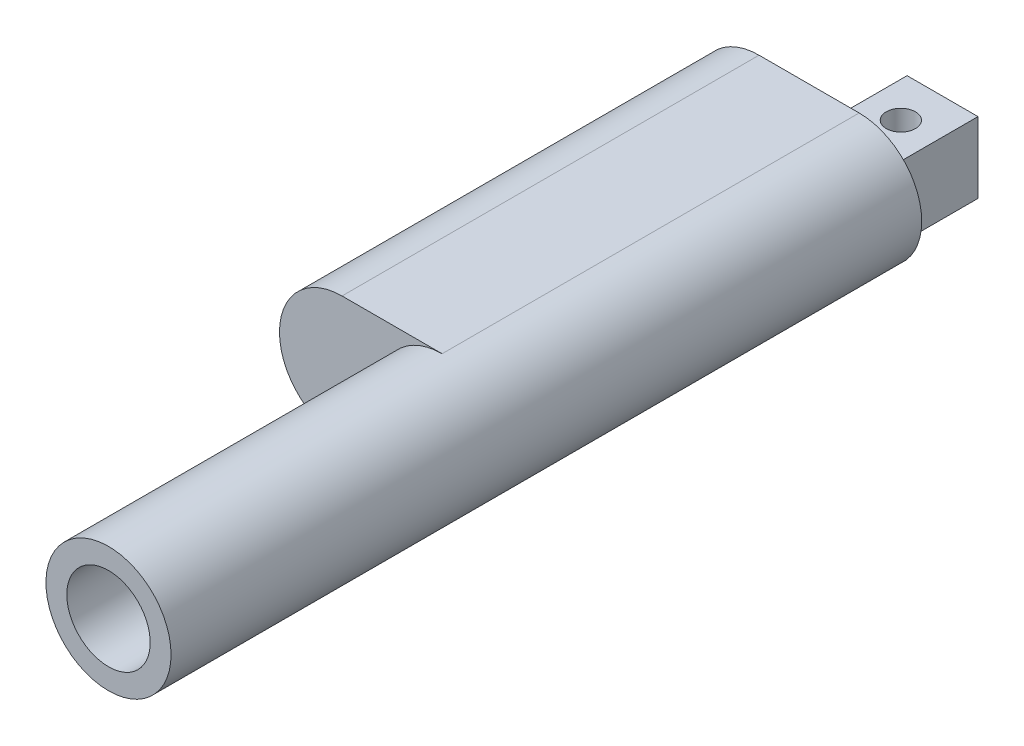
SolidWorks part; units mm, degrees
ref_plane "Plan de face" through (0, 0, 0) normal (0, 0, 1) x (1, 0, 0)
ref_plane "Plan de dessus" through (0, 0, 0) normal (0, 1, 0) x (1, 0, 0)
ref_plane "Plan de droite" through (0, 0, 0) normal (1, 0, 0) x (0, 0, -1)
sketch "Esquisse1" plane through (0, 0, 0) normal (0, 0, 1) x (1, 0, 0)
  circle A0 centre (0, 0) radius 15
  circle A1 centre (0, 0) radius 10
  dimension "D1" = 20
  dimension "D2" = 30
extrude "Boss.-Extru.1" add sketch "Esquisse1" along normal blind 180
sketch "Esquisse2" plane through (0, 0, 0) normal (0, 0, -1) x (-1, 0, 0)
  line L0 (0, 0) -> (24, 0) construction
  line L1 (0, 15) -> (24, 15)
  line L2 (0, -15) -> (24, -15)
  arc A0 (0, 15) -> (0, -15) centre (0, 0) ccw
  arc A1 (24, -15) -> (24, 15) centre (24, 0) ccw
  point P3 (12, 0)
  dimension "D1" = 15
  dimension "D2" = 24
extrude "Boss.-Extru.2" add sketch "Esquisse2" against normal blind 100
sketch "Esquisse3" plane through (0, 0, 0) normal (0, 0, -1) x (-1, 0, 0)
  line L1 (-8.5, 8.5) -> (8.5, 8.5)
  line L2 (-8.5, 8.5) -> (-8.5, -8.5)
  line L3 (-8.5, -8.5) -> (8.5, -8.5)
  line L4 (8.5, 8.5) -> (8.5, -8.5)
  dimension "D1" = 17
  dimension "D2" = 17
  dimension "D3" = 8.5
  dimension "D4" = 8.5
extrude "Boss.-Extru.3" add sketch "Esquisse3" along normal blind 20
sketch "Esquisse4" plane through (0, 8.5, 0) normal (0, 1, 0) x (1, 0, 0)
  line L0 (-8.5, 0) -> (8.5, 0) construction
  circle A0 centre (0, 10) radius 3.5
  dimension "D1" = 7
  dimension "D2" = 10
extrude "Enlèv. mat.-Extru.1" cut sketch "Esquisse4" against normal blind 20
